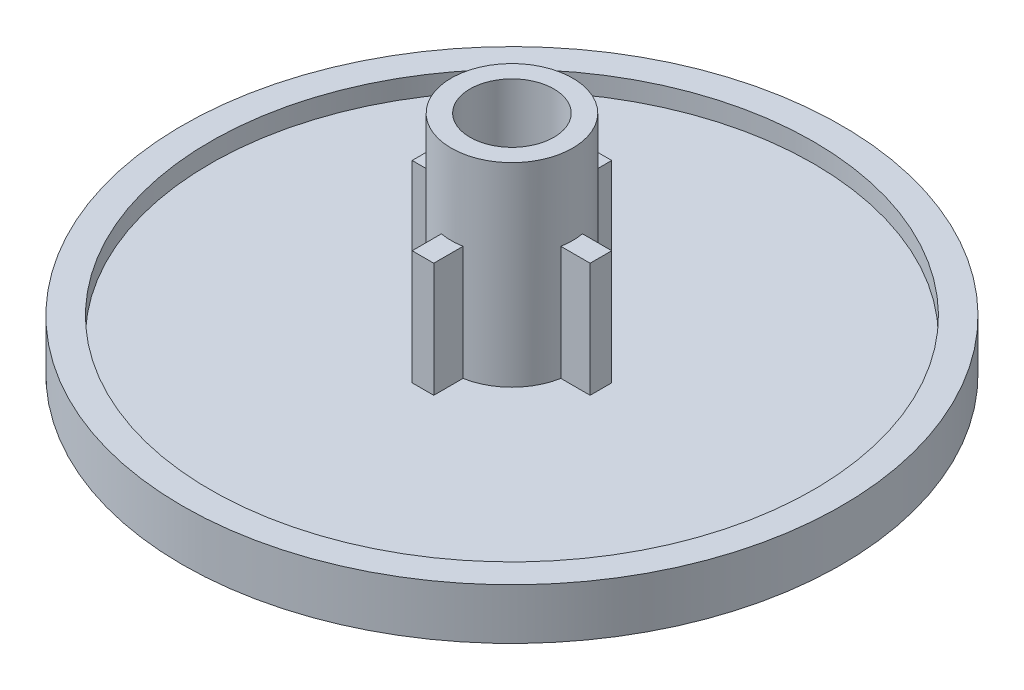
SolidWorks part; units mm, degrees
material "ABS"
ref_plane "Front Plane" through (0, 0, 0) normal (0, 0, 1) x (1, 0, 0)
ref_plane "Top Plane" through (0, 0, 0) normal (0, 1, 0) x (1, 0, 0)
ref_plane "Right Plane" through (0, 0, 0) normal (1, 0, 0) x (0, 0, -1)
sketch "Sketch1" plane through (0, 0, 0) normal (0, 1, 0) x (1, 0, 0)
  circle A0 centre (0, 0) radius 13.1699
  dimension "D1" = 26.3398
extrude "Boss-Extrude1" add sketch "Sketch1" along normal blind 1.27
sketch "Sketch2" plane through (0, 1.27, 0) normal (0, 1, 0) x (1, 0, 0)
  circle A0 centre (0, 0) radius 12.0523
  circle A1 centre (0, 0) radius 13.1699 construction
  circle A3 centre (0, 0) radius 13.1699
  circle A4 centre (0, 0) radius 13.1699
  dimension "D1" = 1.1176
  dimension "D2" = 0
extrude "Boss-Extrude2" add sketch "Sketch2" along normal blind 0.762
sketch "Sketch3" plane through (0, 1.27, 0) normal (0, 1, 0) x (1, 0, 0)
  circle A0 centre (0, 0) radius 2.4257
  dimension "D1" = 4.8514
extrude "Boss-Extrude3" add sketch "Sketch3" along normal blind 7.7724
sketch "Sketch6" plane through (0, 0, 0) normal (0, 0, 1) x (1, 0, 0)
  line L0 (13.1699, 2.032) -> (-13.1699, 2.032) construction
  line L1 (-3.556, 0) -> (3.556, 0)
  line L2 (-3.556, 0) -> (-3.556, 5.842)
  line L3 (-3.556, 5.842) -> (3.556, 5.842)
  line L4 (3.556, 0) -> (3.556, 5.842)
  line L5 (-3.556, 0) -> (3.556, 5.842) construction
  line L6 (-3.556, 5.842) -> (3.556, 0) construction
  line L7 (-13.1699, 0) -> (13.1699, 0) construction
  point P4 (0, 2.921)
  dimension "D1" = 7.112
  dimension "D2" = 3.81
extrude "Boss-Extrude4" add sketch "Sketch6" along normal mid plane 0.8636
sketch "Sketch7" plane through (0, 0, 0) normal (1, 0, 0) x (0, 0, -1)
  line L0 (-13.1699, 0) -> (13.1699, 0) construction
  line L1 (-3.556, 0) -> (3.556, 0)
  line L2 (-3.556, 0) -> (-3.556, 5.842)
  line L3 (-3.556, 5.842) -> (3.556, 5.842)
  line L4 (3.556, 0) -> (3.556, 5.842)
  line L5 (-3.556, 0) -> (3.556, 5.842) construction
  line L6 (-3.556, 5.842) -> (3.556, 0) construction
  line L7 (-0.4318, 5.842) -> (0.4318, 5.842) construction
  point P4 (0, 2.921)
  dimension "D1" = 7.112
extrude "Boss-Extrude5" add sketch "Sketch7" along normal mid plane 0.8636
sketch "Sketch4" plane through (0, 9.0424, 0) normal (0, 1, 0) x (1, 0, 0)
  circle A0 centre (0, 0) radius 1.6764
  dimension "D1" = 3.3528
extrude "Cut-Extrude1" cut sketch "Sketch4" against normal up to surface (7.7724 mm away) up to face at (0, 1.27, 12.0523)
